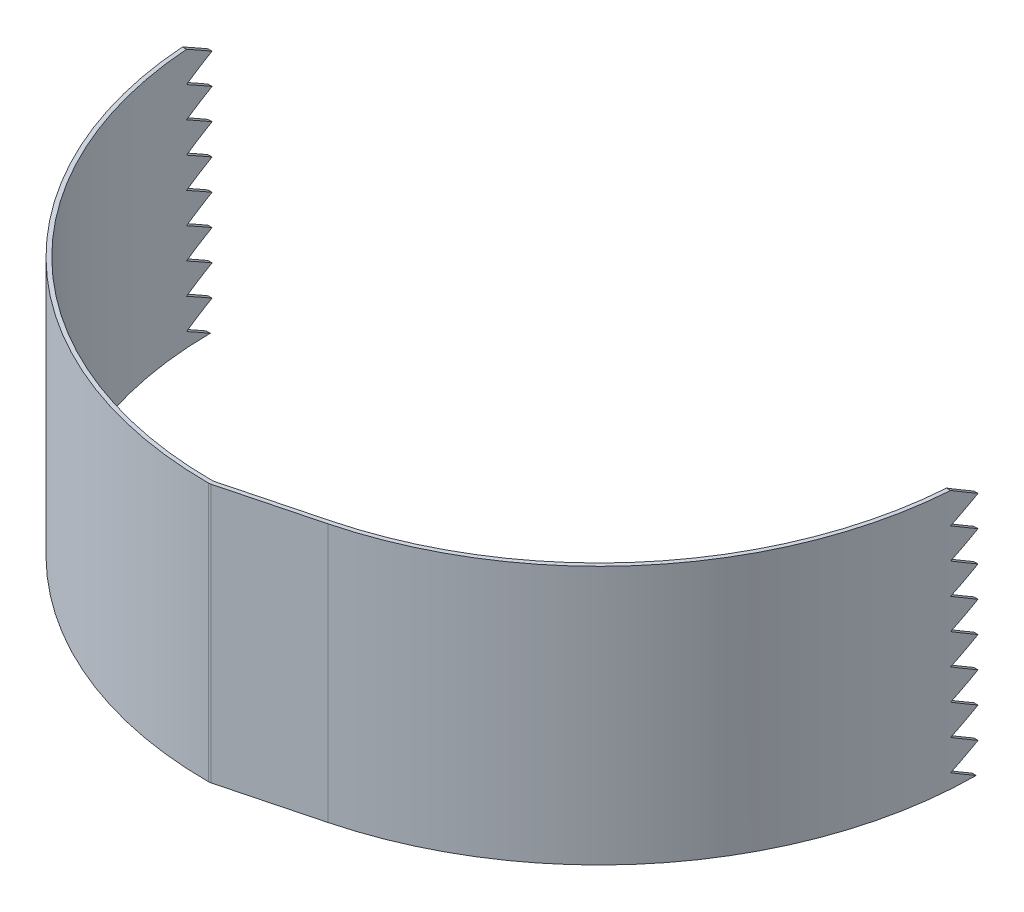
SolidWorks part; units mm, degrees
ref_plane "Front" through (0, 0, 0) normal (0, 0, 1) x (1, 0, 0)
ref_plane "Top" through (0, 0, 0) normal (0, 1, 0) x (1, 0, 0)
ref_plane "Right" through (0, 0, 0) normal (1, 0, 0) x (0, 0, -1)
sketch "Sketch1" plane through (0, 0, 0) normal (0, 1, 0) x (1, 0, 0)
  line L0 (0, -9.2) -> (0, -9.5) construction
  line L1 (-9.5, 0) -> (-9.2, 0) construction
  line L2 (0.0504, -9.4935) -> (2.3179, -8.9032)
  line L3 (0.0632, -9.5935) -> (2.3431, -9)
  line L4 (0.0387, -9.5999) -> (2.3431, -9) construction
  line L5 (0.0257, -9.5) -> (2.3179, -8.9032) construction
  line L6 (-9.6, 0) -> (-9.5, 0)
  line L7 (9.3, 0) -> (9.2, 0)
  circle A0 centre (0, 0) radius 9.2 construction
  arc A1 (-9.5, 0) -> (0.0257, -9.5) centre (0, 0) ccw construction
  circle A2 centre (0, 0) radius 9.5 construction
  arc A3 (-9.5, 0) -> (0, -9.5) centre (0, 0) ccw
  arc A4 (9.2, 0) -> (2.3179, -8.9032) centre (0, 0) cw
  arc A5 (-9.6, 0) -> (0.0131, -9.6) centre (0, 0) ccw
  arc A6 (9.3, 0) -> (2.3431, -9) centre (0, 0) cw
  arc A7 (-9.6, 0) -> (0.0387, -9.5999) centre (0, 0) ccw construction
  arc A8 (0.0131, -9.6) -> (0.0632, -9.5935) centre (0.0128, -9.4) ccw
  arc A9 (-9.5, 0) -> (0.0257, -9.5) centre (0, 0) ccw construction
  arc A10 (0, -9.5) -> (0.0504, -9.4935) centre (0, -9.3) ccw
  dimension "D1" = 18.4
  dimension "D2" = 0.3
  dimension "D3" = 0.1
  dimension "D4" = 0.2
extrude "Boss-Extrude1" add sketch "Sketch1" along normal mid plane 6.35
sketch "Sketch2" plane through (0, 0, 0) normal (1, 0, 0) x (0, 0, -1)
  line L0 (0, 3.55) -> (-0.6495, 3.175)
  line L1 (-0.6495, 3.175) -> (0, 2.8)
  line L2 (0, 3.55) -> (0, 2.8)
  line L3 (0, 3.175) -> (0, -3.175) construction
  line L4 (0, 3.175) -> (-9, 3.175) construction
  line L5 (-0.6495, 2.425) -> (0, 2.05)
  line L6 (0, 2.8) -> (0, 2.05)
  line L7 (0, 2.8) -> (-0.6495, 2.425)
  line L8 (-0.6495, 1.675) -> (0, 1.3)
  line L9 (0, 2.05) -> (0, 1.3)
  line L10 (0, 2.05) -> (-0.6495, 1.675)
  line L11 (-0.6495, 0.925) -> (0, 0.55)
  line L12 (0, 1.3) -> (0, 0.55)
  line L13 (0, 1.3) -> (-0.6495, 0.925)
  line L14 (-0.6495, 0.175) -> (0, -0.2)
  line L15 (0, 0.55) -> (0, -0.2)
  line L16 (0, 0.55) -> (-0.6495, 0.175)
  line L17 (-0.6495, -0.575) -> (0, -0.95)
  line L18 (0, -0.2) -> (0, -0.95)
  line L19 (0, -0.2) -> (-0.6495, -0.575)
  line L20 (-0.6495, -1.325) -> (0, -1.7)
  line L21 (0, -0.95) -> (0, -1.7)
  line L22 (0, -0.95) -> (-0.6495, -1.325)
  line L23 (-0.6495, -2.075) -> (0, -2.45)
  line L24 (0, -1.7) -> (0, -2.45)
  line L25 (0, -1.7) -> (-0.6495, -2.075)
  line L26 (-0.6495, -2.825) -> (0, -3.2)
  line L27 (0, -2.45) -> (0, -3.2)
  line L28 (0, -2.45) -> (-0.6495, -2.825)
  dimension "D1" = 0.75
  dimension "D2" = 60
  dimension "D3" = 30
  dimension "D4" = 9
extrude "Cut-Extrude1" cut sketch "Sketch2" against normal through all both and the other way through all contours L2 L0 L1 | L6 L7 L5 | L9 L10 L8 | L12 L13 L11 | L15 L16 L14 | L18 L19 L17 | L21 L22 L20 | L24 L25 L23 | L27 L28 L26
